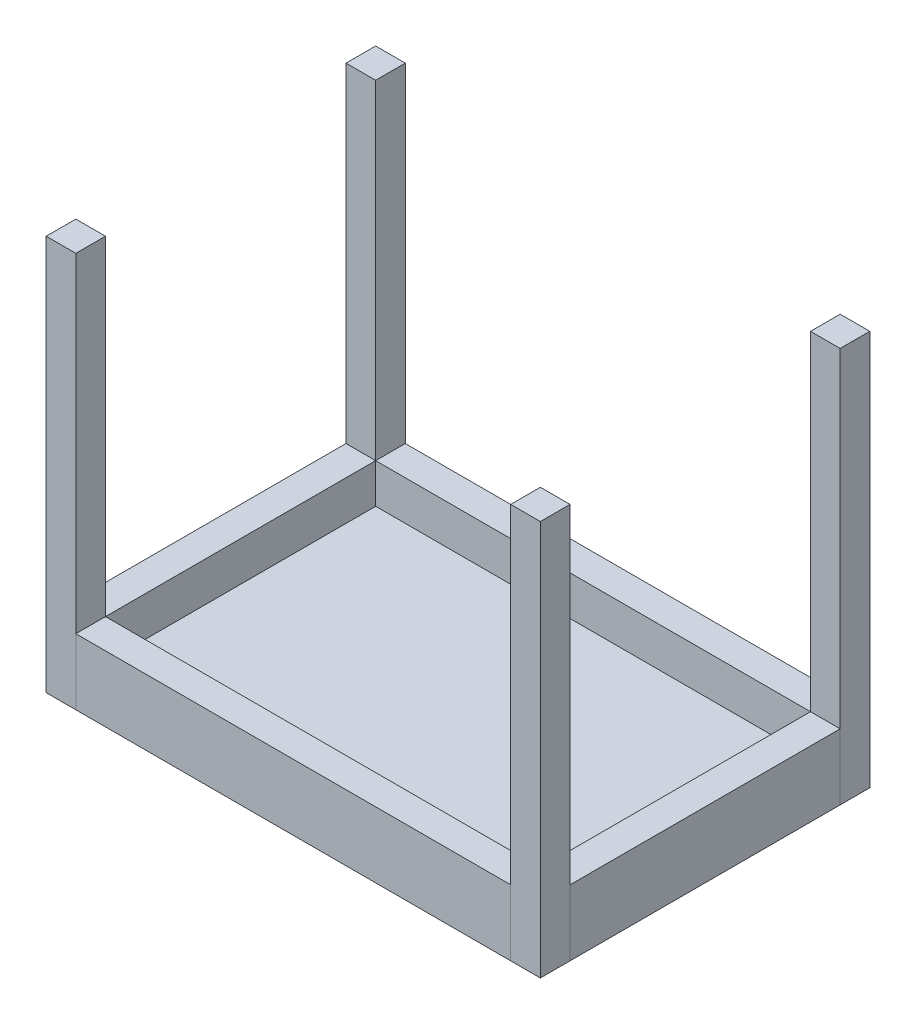
SolidWorks part; units mm, degrees
ref_plane "Front Plane" through (0, 0, 0) normal (0, 0, 1) x (1, 0, 0)
ref_plane "Top Plane" through (0, 0, 0) normal (0, 1, 0) x (1, 0, 0)
ref_plane "Right Plane" through (0, 0, 0) normal (1, 0, 0) x (0, 0, -1)
sketch "Sketch3" plane through (0, 0, 0) normal (0, 0, 1) x (1, 0, 0)
  line L1 (-4.5, -10) -> (4.5, -10)
  line L2 (-4.5, -10) -> (-4.5, 10)
  line L3 (-4.5, 10) -> (4.5, 10)
  line L4 (4.5, -10) -> (4.5, 10)
  line L5 (-4.5, -10) -> (4.5, 10) construction
  line L6 (-4.5, 10) -> (4.5, -10) construction
  point P0 (0, 0)
  dimension "D1" = 9
  dimension "D2" = 20
extrude "Boss-Extrude2" add sketch "Sketch3" along normal blind 82
sketch "Sketch7" plane through (-4.5, 0, 0) normal (-1, 0, 0) x (0, 0, 1)
  line L0 (82, 10) -> (0, 10) construction
  line L1 (82, -10) -> (91, -10)
  line L2 (82, -10) -> (82, 10)
  line L3 (82, 10) -> (91, 10)
  line L4 (91, -10) -> (91, 10)
  dimension "D1" = 9
extrude "Boss-Extrude7" add sketch "Sketch7" along normal blind 132 separate body contours L4 L3 L2 L1
sketch "Sketch8" plane through (-136.5, 0, 0) normal (-1, 0, 0) x (0, 0, 1)
  line L8 (0, 10) -> (0, -10)
  line L9 (82, 10) -> (0, 10)
  line L10 (82, -10) -> (82, 10)
  line L11 (0, -10) -> (82, -10)
  line L12 (0, 10) -> (0, -10)
  line L13 (82, 10) -> (0, 10)
  line L14 (82, -10) -> (82, 10)
  line L15 (0, -10) -> (82, -10)
  dimension "D1" = 0
extrude "Boss-Extrude8" add sketch "Sketch8" along normal blind 9 separate body
sketch "Sketch9" plane through (-4.5, 0, 0) normal (-1, 0, 0) x (0, 0, 1)
  line L0 (82, 10) -> (0, 10) construction
  line L1 (0, -10) -> (-9, -10)
  line L2 (0, -10) -> (0, 10)
  line L3 (0, 10) -> (-9, 10)
  line L4 (-9, -10) -> (-9, 10)
  dimension "D1" = 9
extrude "Boss-Extrude9" add sketch "Sketch9" along normal up to surface (132 mm away) separate body contours L2 L1 L4 L3 up to face at (-136.5, 0, 41)
sketch "Sketch11" plane through (0, 0, 82) normal (0, 0, -1) x (-1, 0, 0)
  line L0 (136.5, -10) -> (136.5, 10) construction
  line L1 (4.5, -10) -> (136.5, -10)
  line L2 (4.5, -10) -> (4.5, -2)
  line L3 (4.5, -2) -> (136.5, -2)
  line L4 (136.5, -10) -> (136.5, -2)
  dimension "D1" = 8
extrude "Boss-Extrude13" add sketch "Sketch11" along normal up to next separate body contours L3 L4 L1 L2
sketch "Sketch12" plane through (0, -10, 0) normal (0, -1, 0) x (1, 0, 0)
  line L1 (-136.5, 91) -> (-145.5, 91)
  line L2 (-136.5, 91) -> (-136.5, 82)
  line L3 (-136.5, 82) -> (-145.5, 82)
  line L4 (-145.5, 91) -> (-145.5, 82)
  line L5 (-4.5, 91) -> (4.5, 91)
  line L6 (-4.5, 91) -> (-4.5, 82)
  line L7 (-4.5, 82) -> (4.5, 82)
  line L8 (4.5, 91) -> (4.5, 82)
  line L9 (4.5, 0) -> (-4.5, 0)
  line L10 (4.5, 0) -> (4.5, -9)
  line L11 (4.5, -9) -> (-4.5, -9)
  line L12 (-4.5, 0) -> (-4.5, -9)
  line L13 (-136.5, -9) -> (-145.5, -9)
  line L14 (-136.5, -9) -> (-136.5, 0)
  line L15 (-136.5, 0) -> (-145.5, 0)
  line L16 (-145.5, -9) -> (-145.5, 0)
extrude "Boss-Extrude14" add sketch "Sketch12" against normal blind 120 separate body
